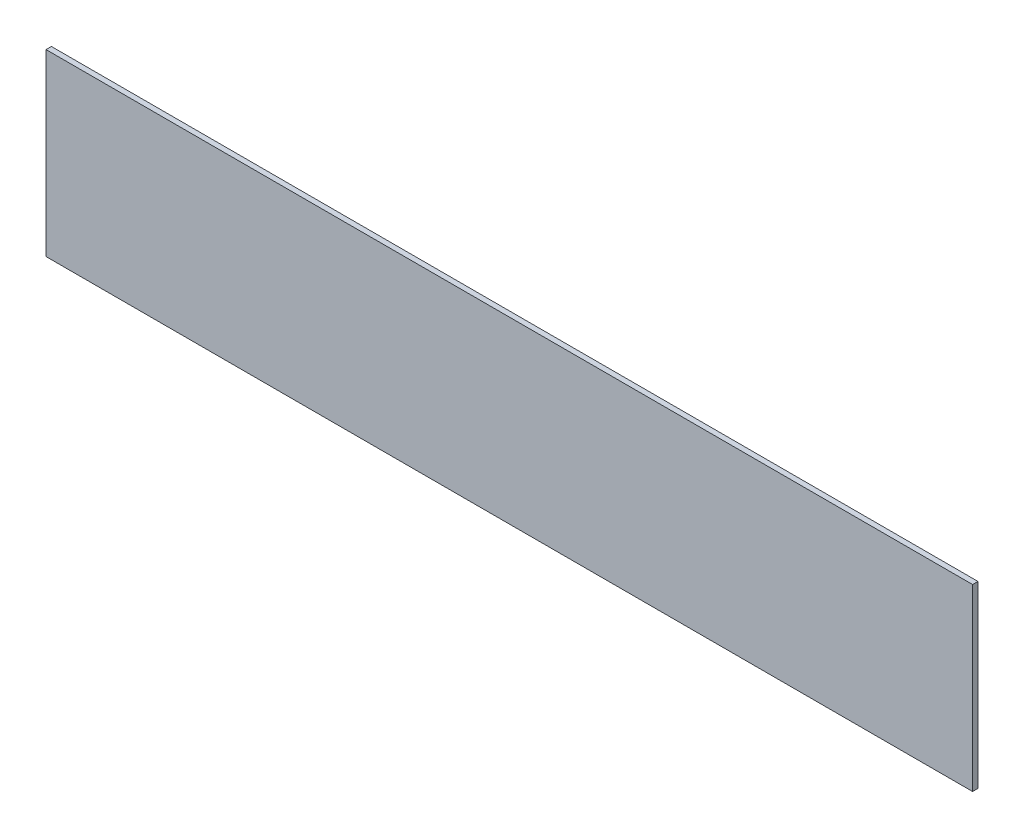
SolidWorks part; units mm, degrees
ref_plane "Front Plane" through (0, 0, 0) normal (0, 0, 1) x (1, 0, 0)
ref_plane "Top Plane" through (0, 0, 0) normal (0, 1, 0) x (1, 0, 0)
ref_plane "Right Plane" through (0, 0, 0) normal (1, 0, 0) x (0, 0, -1)
sketch "Sketch1" plane through (0, 0, 0) normal (0, 0, 1) x (1, 0, 0)
  line L1 (0, 0) -> (41.35, 0)
  line L2 (0, 0) -> (0, 8)
  line L3 (0, 8) -> (41.35, 8)
  line L4 (41.35, 0) -> (41.35, 8)
  dimension "D1" = 41.35
  dimension "D2" = 8
extrude "Boss-Extrude1" add sketch "Sketch1" along normal blind 0.24
